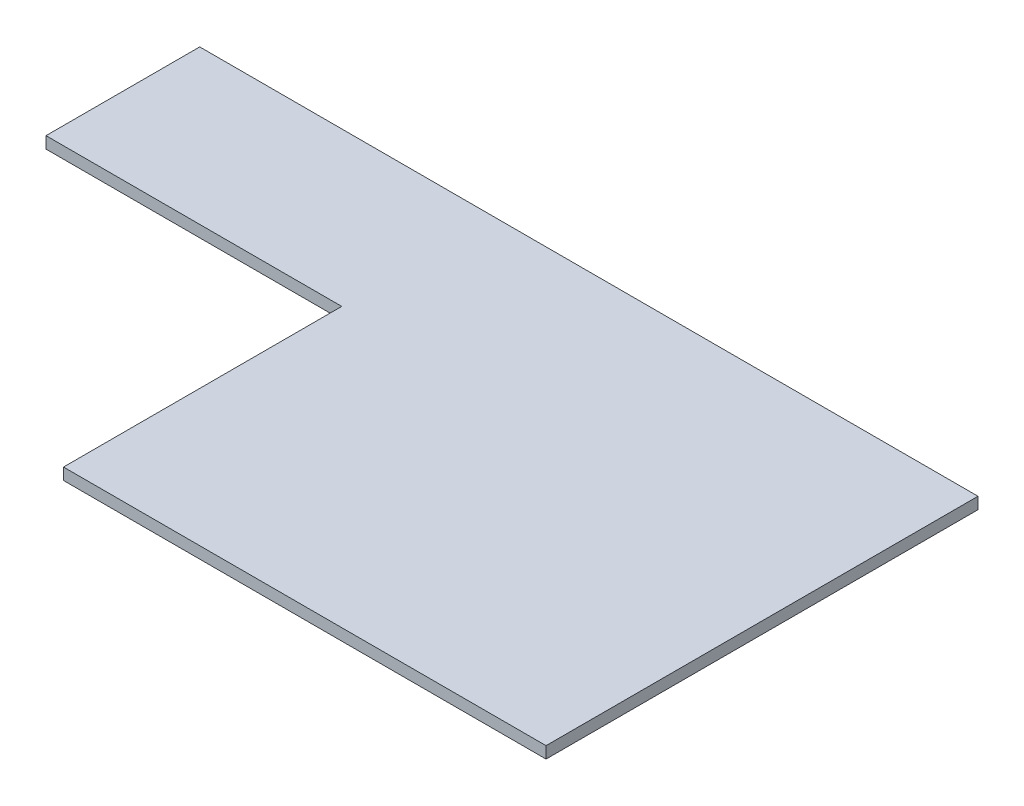
SolidWorks part; units mm, degrees
ref_plane "Front Plane" through (0, 0, 0) normal (0, 0, 1) x (1, 0, 0)
ref_plane "Top Plane" through (0, 0, 0) normal (0, 1, 0) x (1, 0, 0)
ref_plane "Right Plane" through (0, 0, 0) normal (1, 0, 0) x (0, 0, -1)
sketch "Sketch1" plane through (0, 0, 0) normal (0, 1, 0) x (1, 0, 0)
  line L1 (0, 0) -> (-248, 0)
  line L2 (0, 0) -> (0, 222)
  line L3 (0, 222) -> (-400, 222)
  line L4 (-400, 143) -> (-400, 222)
  line L7 (-400, 143) -> (-248, 143)
  line L8 (-248, 0) -> (-248, 143)
  dimension "D1" = 400
  dimension "D2" = 222
  dimension "D3" = 248
  dimension "D4" = 79
extrude "Boss-Extrude1" add sketch "Sketch1" along normal blind 6
